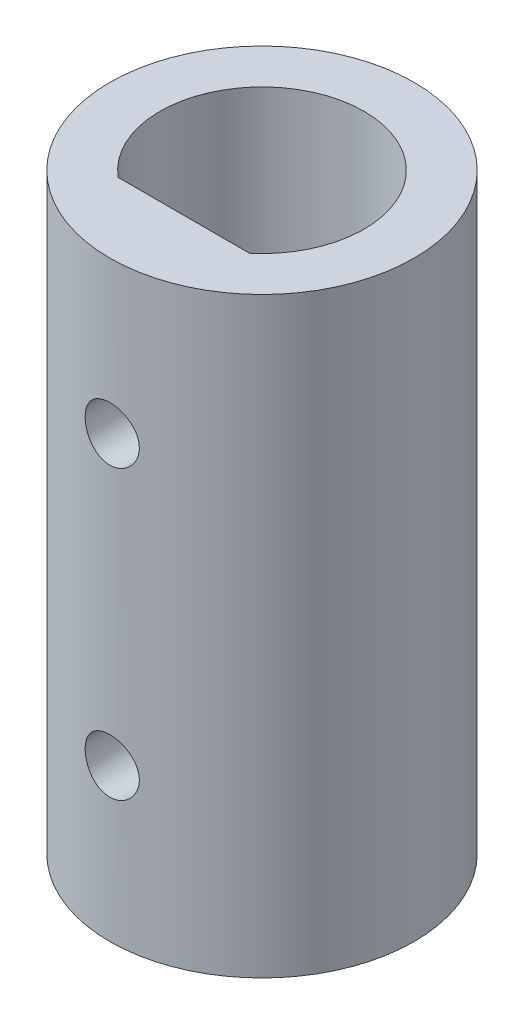
SolidWorks part; units mm, degrees
material "Brass"
ref_plane "Front Plane" through (0, 0, 0) normal (0, 0, 1) x (1, 0, 0)
ref_plane "Top Plane" through (0, 0, 0) normal (0, 1, 0) x (1, 0, 0)
ref_plane "Right Plane" through (0, 0, 0) normal (1, 0, 0) x (0, 0, -1)
sketch "Sketch1" plane through (0, 0, 0) normal (0, 1, 0) x (1, 0, 0)
  line L0 (0, -4.2603) -> (0, -3.2603) construction
  line L1 (-2.7424, -3.2603) -> (2.7424, -3.2603)
  arc A0 (2.7424, -3.2603) -> (-2.7424, -3.2603) centre (0, 0) ccw
  circle A1 centre (0, 0) radius 6.35
  dimension "D1" = 8.5207
  dimension "D2" = 12.7
  dimension "D3" = 1
extrude "Boss-Extrude1" add sketch "Sketch1" along normal blind 24.7
sketch "Sketch3" plane through (0, 0, 3.2603) normal (0, 0, -1) x (-1, 0, 0)
  line L0 (6.35, 24.7) -> (-6.35, 24.7) construction
  line L1 (0, 24.7) -> (0, 0) construction
  line L2 (6.35, 12.35) -> (-6.35, 12.35) construction
  line L3 (6.35, 0) -> (6.35, 24.7) construction
  line L4 (-6.35, 24.7) -> (-6.35, 0) construction
  circle A0 centre (0, 18.35) radius 1.13
  circle A1 centre (0, 6.35) radius 1.13
  dimension "D1" = 2.26
  dimension "D2" = 6.35
extrude "Cut-Extrude1" cut sketch "Sketch3" against normal through all
